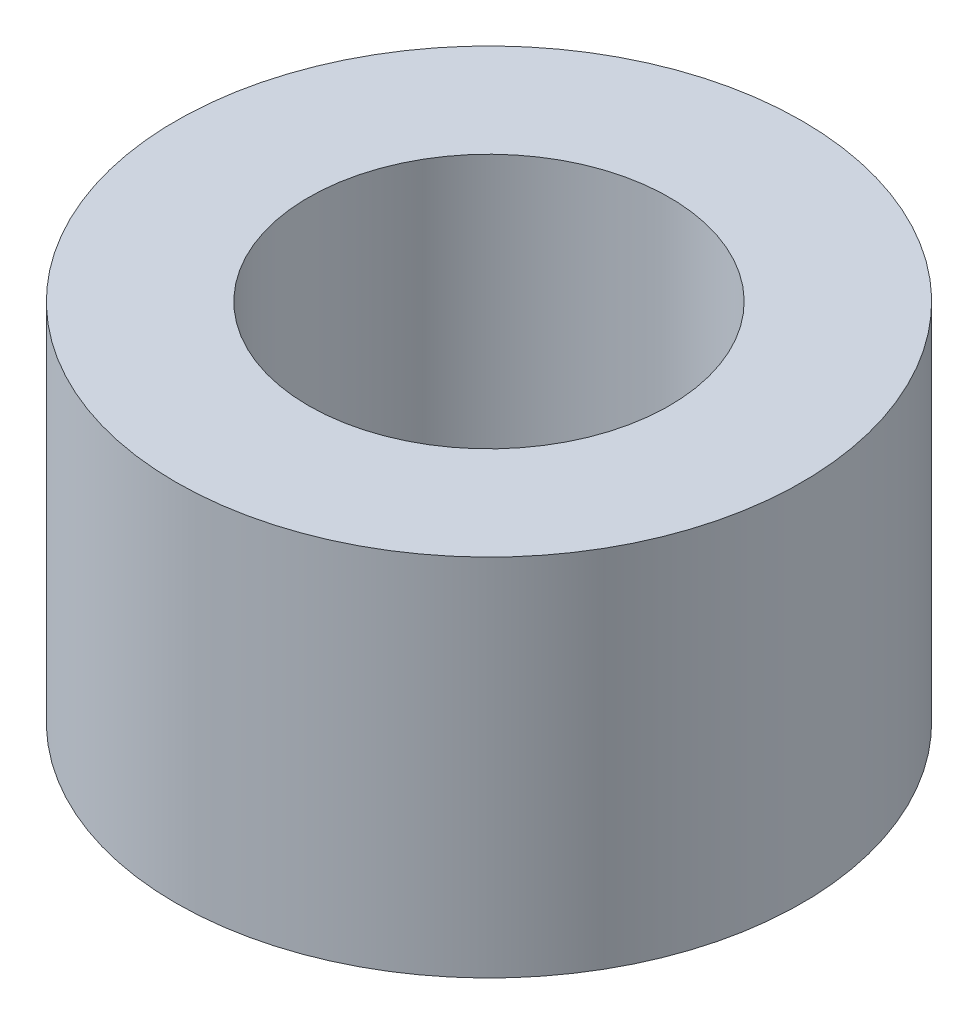
SolidWorks part; units mm, degrees
ref_plane "Front Plane" through (0, 0, 0) normal (0, 0, 1) x (1, 0, 0)
ref_plane "Top Plane" through (0, 0, 0) normal (0, 1, 0) x (1, 0, 0)
ref_plane "Right Plane" through (0, 0, 0) normal (1, 0, 0) x (0, 0, -1)
sketch "Sketch1" plane through (0, 0, 0) normal (0, 1, 0) x (1, 0, 0)
  circle A0 centre (0, 0) radius 4.2934
  circle A1 centre (0, 0) radius 2.475
  dimension "D1" = 4.95
extrude "Boss-Extrude1" add sketch "Sketch1" along normal blind 5
